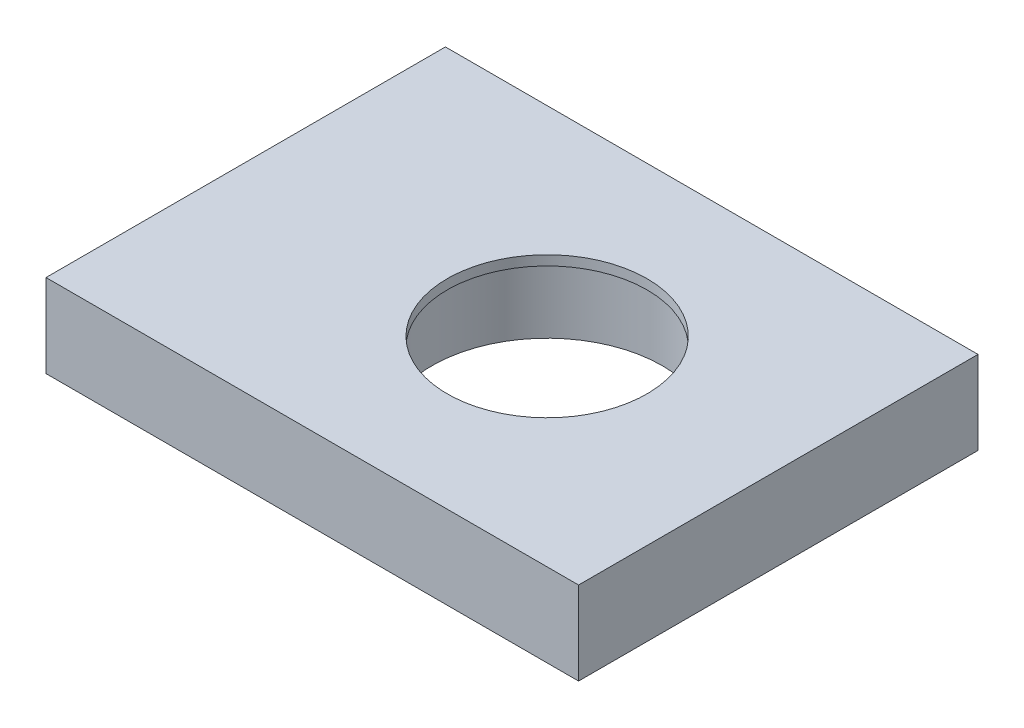
SolidWorks part; units mm, degrees
ref_plane "Front Plane" through (0, 0, 0) normal (0, 0, 1) x (1, 0, 0)
ref_plane "Top Plane" through (0, 0, 0) normal (0, 1, 0) x (1, 0, 0)
ref_plane "Right Plane" through (0, 0, 0) normal (1, 0, 0) x (0, 0, -1)
sketch "Sketch1" plane through (0, 0, 0) normal (0, 1, 0) x (1, 0, 0)
  line L1 (-25.4, -19.05) -> (25.4, -19.05)
  line L2 (-25.4, -19.05) -> (-25.4, 19.05)
  line L3 (-25.4, 19.05) -> (25.4, 19.05)
  line L4 (25.4, -19.05) -> (25.4, 19.05)
  line L5 (-25.4, -19.05) -> (25.4, 19.05) construction
  line L6 (-25.4, 19.05) -> (25.4, -19.05) construction
  point P0 (0, 0)
  dimension "D1" = 38.1
  dimension "D2" = 50.8
extrude "Body" add sketch "Sketch1" along normal blind 7.9375
sketch "Sketch 1" plane through (0, 0, 0) normal (0, -1, 0) x (1, 0, 0)
  line L0 (0, 0) -> (3.3528, 0) construction
  line L2 (-25.4, -19.05) -> (-25.4, 19.05) construction
  circle A0 centre (3.3528, 0) radius 9.525
  dimension "D1" = 19.05
  dimension "D2" = 28.7528
extrude "Thru Hole" cut sketch "Sketch 1" against normal through all
sketch "Sketch4" plane through (0, 0, 0) normal (0, -1, 0) x (1, 0, 0)
  circle A0 centre (3.3528, 0) radius 10.9982
  dimension "D1" = 21.9964
extrude "Bearing Bore" cut sketch "Sketch4" against normal blind 7.0104
sketch "Sketch5" plane through (0, 0, 0) normal (0, -1, 0) x (1, 0, 0)
  line L0 (-21.4249, 14.986) -> (-21.4249, -14.986) construction
  line L1 (-25.4, 0) -> (-17.4498, 0) construction
  line L2 (-25.4, 19.05) -> (-25.4, -19.05) construction
  line L3 (-25.4, -19.05) -> (-17.4498, -19.05) construction
  line L4 (-17.4498, -19.05) -> (-17.4498, 19.05) construction
  line L5 (-17.4498, 19.05) -> (-25.4, 19.05) construction
  line L8 (-25.4, -19.05) -> (-25.4, 19.05) construction
  line L9 (-25.4, 19.05) -> (25.4, 19.05) construction
  line L10 (25.4, -19.05) -> (-25.4, -19.05) construction
  circle A0 centre (-21.4249, 14.986) radius 1.4986
  circle A1 centre (-21.4249, 4.9953) radius 1.4986
  circle A2 centre (-21.4249, -14.986) radius 1.4986
  circle A3 centre (-21.4249, -4.9953) radius 1.4986
  point P23 (-25.4, 0)
  point P26 (-21.4249, 0)
  point P27 (-21.4249, 0)
  dimension "D3" = 2.9972
  dimension "D4" = 2.9972
  dimension "D5" = 2.9972
  dimension "D6" = 2.9972
  dimension "D1" = 7.9502
  dimension "D2" = 29.972
  dimension "D7" = 9.9907
  dimension "D8" = 19.9813
extrude "Dowel Holes" cut sketch "Sketch5" against normal blind 6.5
equation "\"D4@Sketch5\"=\"D3@Sketch5\""
equation "\"D5@Sketch5\"=\"D3@Sketch5\""
equation "\"D6@Sketch5\"=\"D3@Sketch5\""
equation "\"D7@Sketch5\"=\"D2@Sketch5\"/3"
equation "\"D8@Sketch5\"=2*\"D2@Sketch5\"/3"
